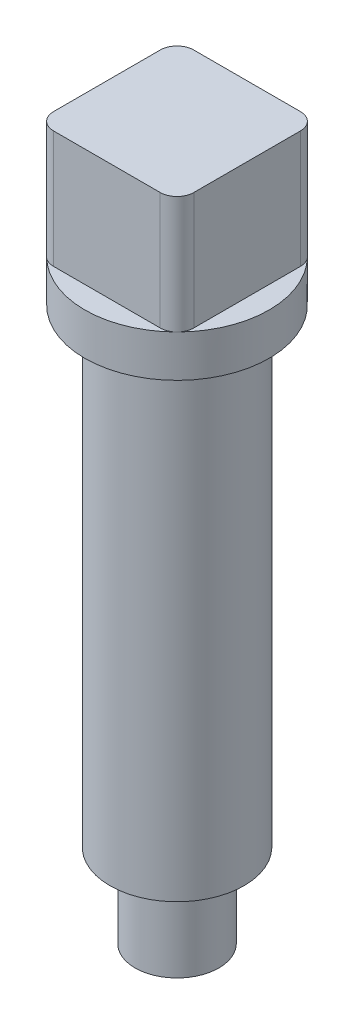
SolidWorks part; units mm, degrees
ref_plane "Front Plane" through (0, 0, 0) normal (0, 0, 1) x (1, 0, 0)
ref_plane "Top Plane" through (0, 0, 0) normal (0, 1, 0) x (1, 0, 0)
ref_plane "Right Plane" through (0, 0, 0) normal (1, 0, 0) x (0, 0, -1)
sketch "Sketch1" plane through (0, 0, 0) normal (0, 0, 1) x (1, 0, 0)
  line L0 (0, 0) -> (5, 0)
  line L1 (5, 0) -> (5, 10)
  line L2 (5, 10) -> (8, 10)
  line L3 (8, 10) -> (8, 66)
  line L4 (8, 66) -> (11, 66)
  line L5 (11, 66) -> (11, 71)
  line L6 (11, 71) -> (0, 71)
  line L7 (0, 71) -> (0, 0) construction
  line L8 (0, 0) -> (0, 71)
  dimension "D1" = 71
  dimension "D2" = 5
  dimension "D3" = 56
  dimension "D4" = 10
  dimension "D5" = 10
  dimension "D6" = 22
  dimension "D7" = 16
revolve "Revolve1" add sketch "Sketch1" angle 360 about L7
cosmetic thread "Cosmetic Thread1" parameters "D2"=13.797
sketch "Sketch2" plane through (0, 71, 0) normal (0, 1, 0) x (1, 0, 0)
  line L1 (6.364, 8.364) -> (-6.364, 8.364)
  line L2 (8.364, 6.364) -> (8.364, -6.364)
  line L3 (6.364, -8.364) -> (-6.364, -8.364)
  line L4 (-8.364, 6.364) -> (-8.364, -6.364)
  line L5 (8.364, 8.364) -> (-8.364, -8.364) construction
  line L6 (8.364, -8.364) -> (-8.364, 8.364) construction
  arc A0 (-6.364, 8.364) -> (-8.364, 6.364) centre (-6.364, 6.364) ccw
  arc A1 (8.364, -6.364) -> (6.364, -8.364) centre (6.364, -6.364) cw
  arc A2 (6.364, 8.364) -> (8.364, 6.364) centre (6.364, 6.364) cw
  arc A3 (-6.364, -8.364) -> (-8.364, -6.364) centre (-6.364, -6.364) cw
  circle A4 centre (0, 0) radius 11 construction
  point P0 (0, 0)
  dimension "D1" = 2
extrude "Boss-Extrude1" add sketch "Sketch2" along normal blind 14
